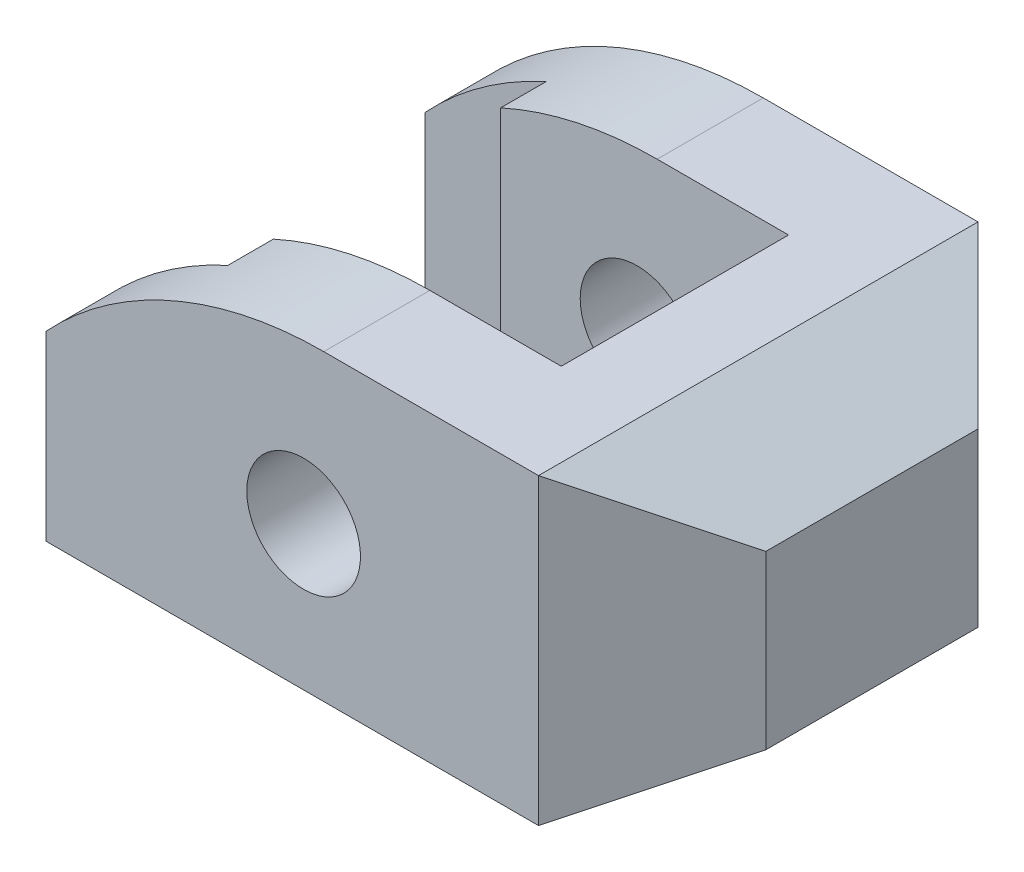
SolidWorks part; units mm, degrees
material "1060 Alloy"
ref_plane "Front Plane" through (0, 0, 0) normal (0, 0, 1) x (1, 0, 0)
ref_plane "Top Plane" through (0, 0, 0) normal (0, 1, 0) x (1, 0, 0)
ref_plane "Right Plane" through (0, 0, 0) normal (1, 0, 0) x (0, 0, -1)
sketch "Sketch1" plane through (0, 0, 0) normal (0, 0, 1) x (1, 0, 0)
  line L0 (0, 0) -> (65, 0)
  line L1 (65, 0) -> (80, 8.6603)
  line L2 (80, 8.6603) -> (80, 31.3397)
  line L3 (80, 31.3397) -> (65, 40)
  line L4 (0, 0) -> (0, 24)
  line L5 (65, 40) -> (36.6606, 40)
  line L6 (0, 19) -> (80, 19) construction
  line L7 (34, 0) -> (34, 19) construction
  arc A0 (36.6606, 40) -> (0, 24) centre (36.6606, -10) ccw
  circle A1 centre (34, 19) radius 7.5
  dimension "D8" = 50
  dimension "D11" = 15
  dimension "D1" = 65
  dimension "D2" = 24
  dimension "D3" = 30
  dimension "D4" = 30
  dimension "D5" = 40
  dimension "D6" = 15
  dimension "D7" = 15
  dimension "D9" = 19
  dimension "D10" = 31
extrude "Boss-Extrude1" add sketch "Sketch1" along normal blind 58
sketch "Sketch2" plane through (0, 0, 0) normal (0, 1, 0) x (1, 0, 0)
  line L0 (0, -58) -> (0, 0) construction
  line L1 (0, -8) -> (16, -8)
  line L2 (0, -8) -> (0, -50)
  line L3 (0, -50) -> (16, -50)
  line L4 (16, -8) -> (16, -50)
  line L5 (36.6606, 0) -> (0, 0) construction
  line L6 (0, -58) -> (36.6606, -58) construction
  dimension "D1" = 8
  dimension "D2" = 8
  dimension "D3" = 16
extrude "Cut-Extrude1" cut sketch "Sketch2" along normal through all
sketch "Sketch3" plane through (0, 0, 0) normal (0, 1, 0) x (1, 0, 0)
  line L0 (16, -50) -> (16, -8) construction
  line L1 (16, -14) -> (54, -14)
  line L2 (16, -14) -> (16, -44)
  line L3 (16, -44) -> (54, -44)
  line L4 (54, -14) -> (54, -44)
  line L5 (65, -58) -> (65, 0) construction
  line L6 (0, -8) -> (16, -8) construction
  line L7 (16, -50) -> (0, -50) construction
  dimension "D1" = 11
  dimension "D2" = 6
  dimension "D3" = 6
extrude "Cut-Extrude2" cut sketch "Sketch3" along normal through all
sketch "Sketch4" plane through (0, 0, 0) normal (0, 1, 0) x (1, 0, 0)
  line L0 (65, 0) -> (80, -15)
  line L1 (80, -58) -> (80, 0) construction
  line L2 (80, -15) -> (80, 0)
  line L3 (80, 0) -> (65, 0)
  line L4 (65, -58) -> (80, -43)
  line L5 (80, -43) -> (80, -58)
  line L6 (80, -58) -> (65, -58)
  line L7 (65, 0) -> (36.6606, 0) construction
  line L8 (65, -58) -> (36.6606, -58) construction
  dimension "D1" = 45
  dimension "D2" = 45
extrude "Cut-Extrude3" cut sketch "Sketch4" along normal through all
equation "\"a\"= 58mm"
equation "\"b\"= 40mm"
equation "\"c\"= 65mm"
